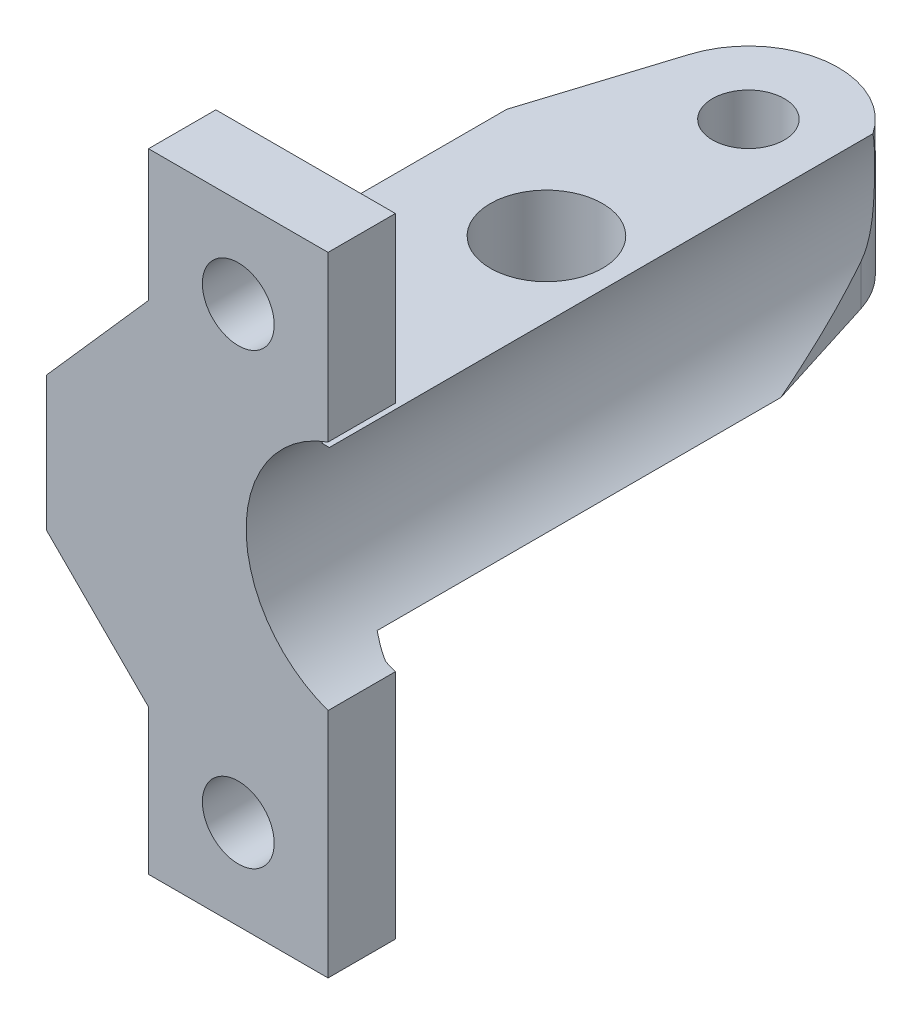
SolidWorks part; units mm, degrees
ref_plane "Спереди" through (0, 0, 0) normal (0, 0, 1) x (1, 0, 0)
ref_plane "Сверху" through (0, 0, 0) normal (0, 1, 0) x (1, 0, 0)
ref_plane "Справа" through (0, 0, 0) normal (1, 0, 0) x (0, 0, -1)
sketch "Эскиз1" plane through (0, 0, 0) normal (0, 0, 1) x (1, 0, 0)
  line L1 (0, 0) -> (-8, 0)
  line L2 (0, 0) -> (0, -28)
  line L3 (0, -28) -> (-8, -28)
  line L4 (-8, 0) -> (-8, -28)
  dimension "D1" = 28
  dimension "D2" = 8
extrude "Бобышка-Вытянуть1" add sketch "Эскиз1" along normal blind 3
ref_plane "Плоскость1" through (0, -14, 0) normal (0, 1, 0) x (1, 0, 0)
sketch "Эскиз2" plane through (0, -14, 0) normal (0, 1, 0) x (1, 0, 0)
  line L0 (-6.77, 7.2704) -> (-6.77, -49992.7296) construction
  line L1 (-7.1566, 13.5) -> (-50007.1566, 13.5) construction
  line L5 (-1, 9.5) -> (-1, 17.5)
  line L6 (-1, 17.5) -> (-2.955, 23.7025)
  line L7 (-10.585, 23.7025) -> (-12.54, 17.5)
  line L8 (-12.54, 17.5) -> (-12.54, 9.5)
  line L11 (0, -3) -> (0, 0) construction
  line L12 (0, 0) -> (-8, 0) construction
  line L16 (0, 0) -> (0, -3)
  line L17 (0, -3) -> (-12.54, -3)
  line L18 (-12.54, -3) -> (-12.54, 9.5)
  line L19 (-1, 9.5) -> (-1, 0)
  line L20 (-1, 0) -> (0, 0)
  circle A0 centre (-6.77, 22.5) radius 1.6
  circle A1 centre (-6.77, 4.5) radius 1.6
  circle A2 centre (-6.77, 13.5) radius 2.5
  arc A4 (-2.955, 23.7025) -> (-10.585, 23.7025) centre (-6.77, 22.5) ccw
  point P11 (-12.54, 13.5)
  dimension "D2" = 4
  dimension "D10" = 3.2
  dimension "D11" = 3.2
  dimension "D12" = 5
  dimension "D3" = 11.54
  dimension "D4" = 18
  dimension "D5" = 9
  dimension "D6" = 5.77
  dimension "D7" = 5.77
  dimension "D8" = 8
  dimension "D9" = 8
  dimension "D14" = 1
  dimension "D15" = 4.5
extrude "Бобышка-Вытянуть2" add sketch "Эскиз2" against normal blind 3 and the other way blind 3
sketch "Эскиз3" plane through (0, 0, 3) normal (0, 0, 1) x (1, 0, 0)
  line L1 (-8, 0) -> (-8, -11) construction
  line L2 (-8, -11) -> (-1, -11) construction
  circle A1 centre (1.85, -12.5) radius 5.5
  dimension "D3" = 5.5
  dimension "D1" = 1.5
  dimension "D2" = 9.85
extrude "Вырез-Вытянуть1" cut sketch "Эскиз3" against normal through all and the other way through all
sketch "Эскиз4" plane through (0, 0, 3) normal (0, 0, 1) x (1, 0, 0)
  line L0 (-12.54, -11) -> (-8, -5.8556)
  line L1 (-8, 0) -> (-8, -11) construction
  line L2 (-8, -5.8556) -> (-8, -21.54)
  line L3 (-8, -17) -> (-8, -28) construction
  line L4 (-8, -21.54) -> (-12.54, -17)
  line L5 (-12.54, -17) -> (-12.54, -11) construction
  line L6 (-12.54, -17) -> (-8, -17) construction
  line L7 (-12.54, -17) -> (-12.54, -11)
  dimension "D1" = 41.429
  dimension "D2" = 45
extrude "Бобышка-Вытянуть3" add sketch "Эскиз4" against normal up to surface (3 mm away) up to face at (-3.9775, -5.7806, 0)
sketch "Эскиз6" plane through (0, 0, 0) normal (0, 0, -1) x (-1, 0, 0)
  line L0 (8, -28) -> (0, -28) construction
  line L1 (0, 0) -> (8, 0) construction
  circle A0 centre (4, -4) radius 1.6
  circle A1 centre (4, -24) radius 1.6
  point P6 (4, -28)
  dimension "D1" = 3.2
  dimension "D2" = 3.2
  dimension "D3" = 4
  dimension "D4" = 4
extrude "Вырез-Вытянуть2" cut sketch "Эскиз6" against normal through all
chamfer "Фаска1" distance 0.5 angle 45 2 edges at (-6.9261, -17, 0) (-7.9908, -11, 0)
